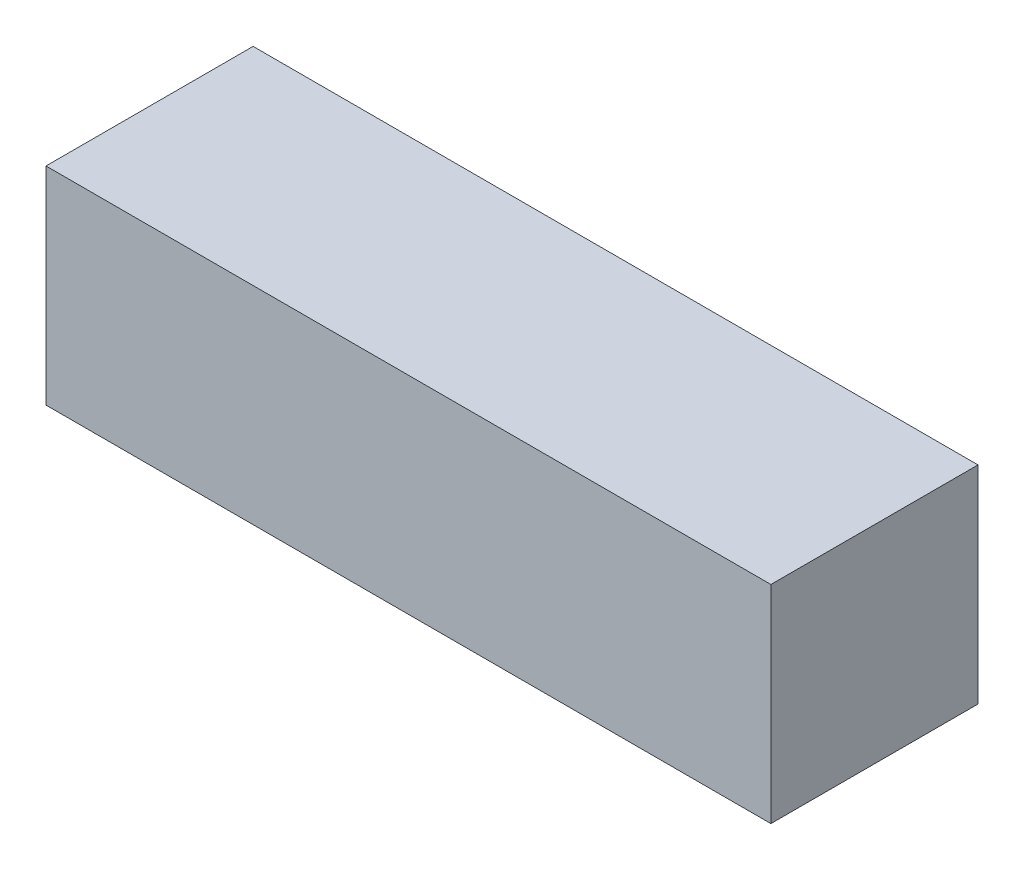
SolidWorks part; units mm, degrees
ref_plane "Front Plane" through (0, 0, 0) normal (0, 0, 1) x (1, 0, 0)
ref_plane "Top Plane" through (0, 0, 0) normal (0, 1, 0) x (1, 0, 0)
ref_plane "Right Plane" through (0, 0, 0) normal (1, 0, 0) x (0, 0, -1)
sketch "Sketch1" plane through (0, 0, 0) normal (0, 1, 0) x (1, 0, 0)
  line L1 (0, 0) -> (177.8, 0)
  line L2 (0, 0) -> (0, 50.8)
  line L3 (0, 50.8) -> (177.8, 50.8)
  line L4 (177.8, 0) -> (177.8, 50.8)
  dimension "D1" = 50.8
  dimension "D2" = 177.8
extrude "Boss-Extrude1" add sketch "Sketch1" along normal blind 50.8
